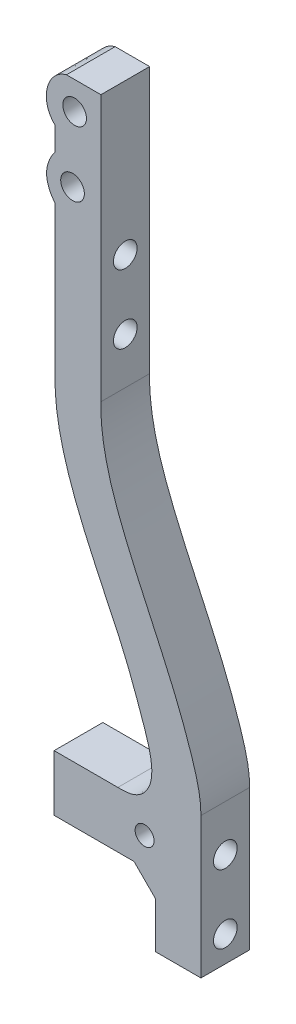
SolidWorks part; units mm, degrees
ref_plane "Piano frontale" through (0, 0, 0) normal (0, 0, 1) x (1, 0, 0)
ref_plane "Piano superiore" through (0, 0, 0) normal (0, 1, 0) x (1, 0, 0)
ref_plane "Piano destro" through (0, 0, 0) normal (1, 0, 0) x (0, 0, -1)
sketch "Schizzo1" plane through (0, 0, 0) normal (0, 0, 1) x (1, 0, 0)
  line L0 (5.7741, 81.0051) -> (9.4205, 81.0051)
  line L1 (9.4205, 81.0051) -> (9.4205, 52.896)
  line L2 (4.5703, 75.8027) -> (4.5703, 73.3384)
  line L3 (4.5703, 68.659) -> (4.5703, 52.896)
  line L4 (11.209, 18.4867) -> (4.474, 18.4867)
  line L5 (4.474, 18.4867) -> (4.474, 12.5612)
  line L6 (4.474, 12.5612) -> (12.918, 12.5612)
  line L7 (12.918, 12.5612) -> (15.1802, 10.299)
  line L8 (15.1802, 10.299) -> (15.1802, 5.4315)
  line L9 (15.1802, 5.4315) -> (19.9932, 5.4315)
  line L10 (19.9932, 5.4315) -> (19.9932, 20.304)
  circle A0 centre (6.6426, 78.0592) radius 1.3459 construction
  circle A1 centre (6.4205, 71.0592) radius 1.4292 construction
  circle A2 centre (14.0356, 15.5003) radius 1
  spline S0 degree 3 poles (5.7741, 81.0051) (3.6381, 80.4272) (2.8873, 77.3788) (4.5703, 75.8027) knots 0 0 0 0 1 1 1 1
  spline S1 degree 3 poles (4.5703, 68.659) (4.0434, 69.2867) (3.2969, 70.987) (4.0685, 72.6681) (4.5703, 73.3384) knots 0 0 0 0 0.492974 1 1 1 1
  spline S2 degree 3 poles (19.9932, 20.304) (20.0004, 21.9376) (19.1363, 25.0954) (17.2511, 30.1999) (14.841, 35.3768) (11.4071, 42.842) (9.3213, 48.6422) (9.4205, 52.896) knots 0 0 0 0 0.139683 0.283827 0.472966 0.635703 1 1 1 1
  spline S3 degree 3 poles (4.5703, 52.896) (4.501, 49.5436) (5.9329, 43.955) (9.2188, 36.724) (11.988, 31.1141) (13.6522, 26.4175) (14.7893, 23.1606) (14.8718, 20.7392) (13.9988, 19.2186) (12.6776, 18.4802) (11.7053, 18.4867) (11.209, 18.4867) knots 0 0 0 0 0.258728 0.443278 0.618371 0.74514 0.830875 0.886814 0.92735 0.960443 1 1 1 1
extrude "Estrusione-Estrusione1" add sketch "Schizzo1" along normal blind 5.15
hole_wizard "Foro filettato M3x0.5-1" positions "Schizzo3" profile "Schizzo2" tap size "M3x0.5" standard "Ansi Metric" end condition through all
sketch "Schizzo3" plane through (0, 0, 5.15) normal (0, 0, 1) x (1, 0, 0)
  circle A0 centre (6.4205, 71.0592) radius 1.4292 construction
  circle A1 centre (6.6426, 78.0592) radius 1.3459 construction
  point P0 (6.6426, 78.0592)
  point P2 (6.4205, 71.0592)
sketch "Schizzo2" plane through (6.6426, 78.0592, 5.15) normal (1, 0, 0) x (0, -1, 0)
  line L0 (0, 0) -> (0, 5.15)
  line L1 (0, 5.15) -> (1.25, 5.15)
  line L2 (1.25, 5.15) -> (1.25, 0)
  line L5 (1.25, 0) -> (0, 0)
  line L11 (0, -6.35) -> (0, 107.95) construction
  dimension "Thru Tap Drill Dia." = 2.5
  dimension "Thru Tap Drill Depth" = 5.15
cosmetic thread "Filettatura del foro1"
cosmetic thread "Filettatura del foro2"
hole_wizard "Foro filettato M3x0.5-2" positions "Schizzo5" profile "Schizzo4" tap size "M3x0.5" standard "Ansi Metric" end condition through all
sketch "Schizzo5" plane through (19.9932, 0, 0) normal (1, 0, 0) x (0, 0, -1)
  line L0 (-2.575, 81.0051) -> (-2.575, 5.4315) construction
  line L1 (-5.15, 81.0051) -> (0, 81.0051) construction
  line L2 (-5.15, 5.4315) -> (0, 5.4315) construction
  point P0 (-2.575, 65.0651)
  point P2 (-2.575, 57.8051)
  point P4 (-2.575, 15.4315)
  point P6 (-2.575, 8.1715)
  dimension "D1" = 7.26
  dimension "D2" = 7.26
  dimension "D3" = 23.2
  dimension "D4" = 10
sketch "Schizzo4" plane through (19.9932, 65.0651, 2.575) normal (0, 1, 0) x (0, 0, -1)
  line L0 (0, 0) -> (0, 16.7305)
  line L1 (0, 16.7305) -> (1.25, 16.7305)
  line L2 (1.25, 16.7305) -> (1.25, 0)
  line L5 (1.25, 0) -> (0, 0)
  line L11 (0, -6.35) -> (0, 107.95) construction
  dimension "Thru Tap Drill Dia." = 2.5
  dimension "Thru Tap Drill Depth" = 16.7305
cosmetic thread "Filettatura del foro3"
cosmetic thread "Filettatura del foro4"
cosmetic thread "Filettatura del foro5"
cosmetic thread "Filettatura del foro6"
